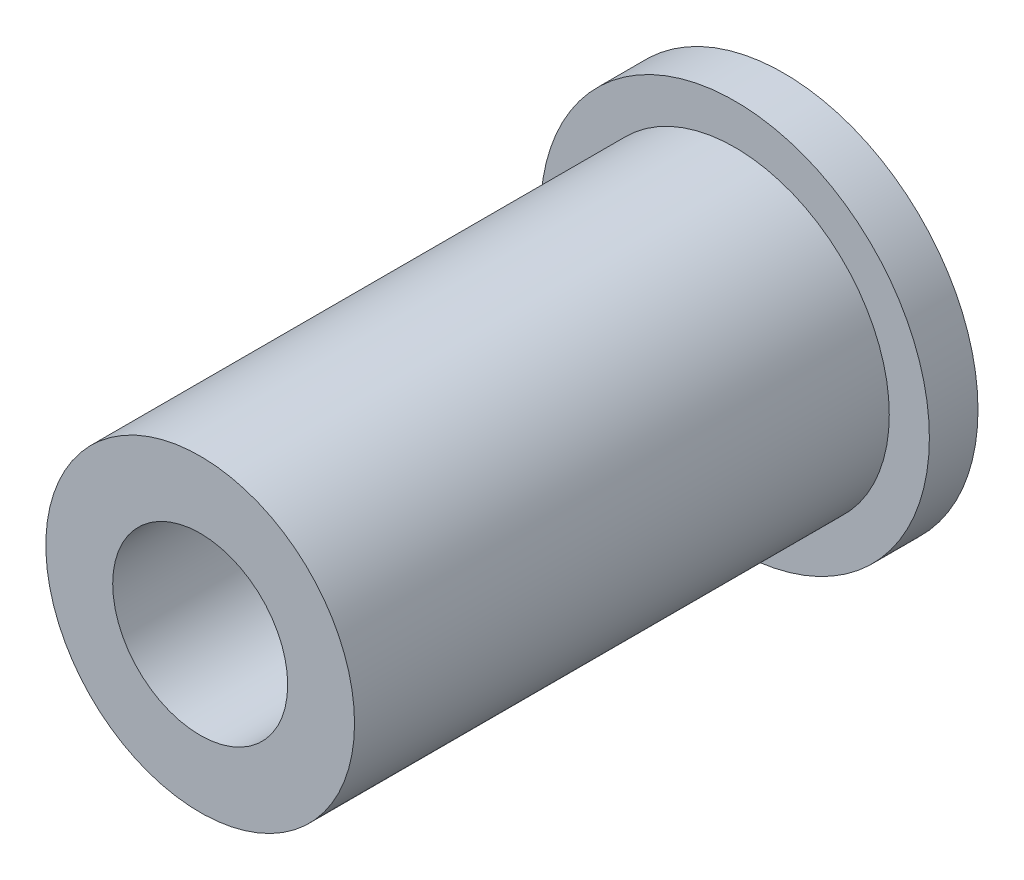
SolidWorks part; units mm, degrees
material "1060 Alloy"
ref_plane "Front Plane" through (0, 0, 0) normal (0, 0, 1) x (1, 0, 0)
ref_plane "Top Plane" through (0, 0, 0) normal (0, 1, 0) x (1, 0, 0)
ref_plane "Right Plane" through (0, 0, 0) normal (1, 0, 0) x (0, 0, -1)
sketch "Sketch1" plane through (0, 0, 0) normal (0, 0, 1) x (1, 0, 0)
  circle A0 centre (0, 0) radius 4
  dimension "D1" = 8
extrude "Boss-Extrude1" add sketch "Sketch1" along normal blind 12
sketch "Sketch2" plane through (0, 0, 12) normal (0, 0, 1) x (1, 0, 0)
  circle A0 centre (0, 0) radius 3.175
  circle A1 centre (0, 0) radius 4
  dimension "D1" = 8
  dimension "D2" = 6.35
extrude "Cut-Extrude1" cut sketch "Sketch2" against normal blind 11
sketch "Sketch5" plane through (0, 0, 0) normal (0, 0, -1) x (-1, 0, 0)
  circle A0 centre (0, 0) radius 1.8
  dimension "D1" = 3.6
extrude "Cut-Extrude2" cut sketch "Sketch5" against normal through all
sketch "Sketch6" plane through (0, 0, 0) normal (0, 0, -1) x (-1, 0, 0)
  circle A0 centre (0, 0) radius 2.8
  dimension "D1" = 5.6
extrude "Cut-Extrude3" cut sketch "Sketch6" against normal blind 4.5
